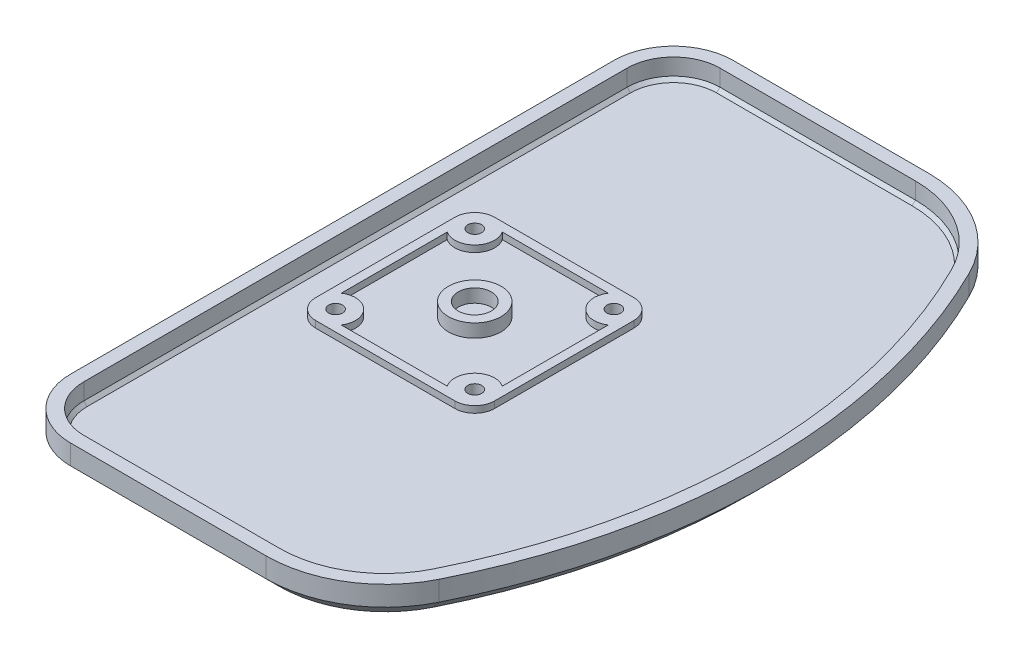
SolidWorks part; units mm, degrees
material "ABS"
ref_plane "Front" through (0, 0, 0) normal (0, 0, 1) x (1, 0, 0)
ref_plane "Top" through (0, 0, 0) normal (0, 1, 0) x (1, 0, 0)
ref_plane "Right" through (0, 0, 0) normal (1, 0, 0) x (0, 0, -1)
sketch "ｽｹｯﾁ1" plane through (0, 0, 0) normal (0, 1, 0) x (1, 0, 0)
  line L0 (-20, 0) -> (44, 0) construction
  line L1 (-20, 50) -> (28.8331, 50)
  line L2 (-20, 50) -> (-20, -50)
  line L3 (-20, -50) -> (28.8331, -50)
  line L5 (-20, 50) -> (22.854, -57.135) construction
  line L6 (-20, -50) -> (29.8928, 74.732) construction
  arc A0 (28.8331, -50) -> (28.8331, 50) centre (-46, 0) ccw
  point P0 (0, 0)
  dimension "D2" = 180
  dimension "D3" = 0
  dimension "D1" = 100
  dimension "D4" = 64
  dimension "D5" = 0
  dimension "D6" = 20
extrude "ﾎﾞｽ - 押し出し1" add sketch "ｽｹｯﾁ1" along normal blind 5
fillet "ﾌｨﾚｯﾄ1" radius 9 2 edges at (-20, 2.5, -50) (-20, 2.5, 50)
fillet "ﾌｨﾚｯﾄ2" radius 18 2 edges at (28.8331, 2.5, -50) (28.8331, 2.5, 50)
shell "ｼｪﾙ1" thickness 2
chamfer "面取り1" distance 0.5 angle 45 8 edges at (26.9308, 2, 45.5974) (3.749, 2, 48) (42, 2, 0) (-15.9497, 2, 45.9497) (26.9308, 2, -45.5974) (-18, 2, 0) (3.749, 2, -48) (-15.9497, 2, -45.9497)
chamfer "面取り2" distance 2 angle 45 8 edges at (44, 0, 0) (27.9849, 0, -47.2971) (27.9849, 0, 47.2971) (3.749, 0, -50) (3.749, 0, 50) (-17.364, 0, -47.364) (-17.364, 0, 47.364) (-20, 0, 0)
sketch "ｽｹｯﾁ2" plane through (0, 2, 0) normal (0, 1, 0) x (1, 0, 0)
  line L1 (-13.5, 13.5) -> (13.5, 13.5)
  line L2 (-13.5, 13.5) -> (-13.5, -13.5)
  line L3 (-13.5, -13.5) -> (13.5, -13.5)
  line L4 (13.5, 13.5) -> (13.5, -13.5)
  line L5 (-13.5, 13.5) -> (13.5, -13.5) construction
  line L6 (-13.5, -13.5) -> (13.5, 13.5) construction
  point P0 (0, 0)
  dimension "D1" = 27
  dimension "D2" = 27
extrude "ﾎﾞｽ - 押し出し2" add sketch "ｽｹｯﾁ2" along normal blind 1
sketch "ｽｹｯﾁ3" plane through (0, 3, 0) normal (0, 1, 0) x (1, 0, 0)
  circle A0 centre (0, 0) radius 3.975
  dimension "D1" = 7.95
extrude "ﾎﾞｽ - 押し出し3" add sketch "ｽｹｯﾁ3" along normal blind 1
fillet "ﾌｨﾚｯﾄ3" radius 3 4 edges at (-13.5, 2.5, -13.5) (13.5, 2.5, -13.5) (13.5, 2.5, 13.5) (-13.5, 2.5, 13.5)
hole_wizard "M2 なべ頭ねじ用座ぐり穴1" positions "ｽｹｯﾁ4" profile "ｽｹｯﾁ5" counterbore size "M2" standard "ISO" end condition up to next
sketch "ｽｹｯﾁ4" plane through (0, 0, 0) normal (0, -1, 0) x (-1, 0, 0)
  point P0 (10.5, 10.5)
  dimension "D1" = 10.5
  dimension "D2" = 10.5
sketch "ｽｹｯﾁ5" plane through (-10.5, 0, -10.5) normal (1, 0, 0) x (0, 0, -1)
  line L0 (0, 0) -> (0, 3)
  line L1 (0, 3) -> (1.05, 3)
  line L3 (1.05, 3) -> (1.05, 1)
  line L4 (1.05, 1) -> (1.9, 1)
  line L5 (1.9, 1) -> (1.9, 0)
  line L7 (1.9, 0) -> (0, 0)
  line L11 (0, -6.35) -> (0, 107.95) construction
  dimension "通し穴の直径" = 2.1
  dimension "通し穴の深さ" = 3
  dimension "座ぐり穴の直径" = 3.8
  dimension "座ぐり穴の深さ" = 1
pattern_circular "円形ﾊﾟﾀｰﾝ1" count 4 over 360 about axis through (0, 0, 0) along (0, 1, 0) of "M2 なべ頭ねじ用座ぐり穴1"
sketch "ｽｹｯﾁ6" plane through (0, 3, 0) normal (0, 1, 0) x (1, 0, 0)
  line L0 (-13.5, 10.5) -> (-13.5, -10.5) construction
  line L1 (12.15, -12.15) -> (-12.15, -12.15)
  line L2 (12.15, -12.15) -> (12.15, 12.15)
  line L3 (12.15, 12.15) -> (-12.15, 12.15)
  line L4 (-12.15, -12.15) -> (-12.15, 12.15)
  line L5 (12.15, -12.15) -> (-12.15, 12.15) construction
  line L6 (12.15, 12.15) -> (-12.15, -12.15) construction
  circle A0 centre (-10.5, 10.5) radius 3
  circle A1 centre (10.5, 10.5) radius 3
  circle A2 centre (-10.5, -10.5) radius 3
  circle A3 centre (10.5, -10.5) radius 3
  circle A4 centre (0, 0) radius 3.975
  point P12 (0, 0)
  circle M7 centre (0, 0) radius 3.975
  dimension "D1" = 6
  dimension "D2" = 6
  dimension "D3" = 6
  dimension "D4" = 6
  dimension "D6" = 7.95
  dimension "D5" = 1.35
extrude "ｶｯﾄ - 押し出し1" cut sketch "ｽｹｯﾁ6" against normal up to surface (1 mm away) contours A3 L2 A1 L3 A0 L4 A2 L1 M7
sketch "ｽｹｯﾁ7" plane through (0, 4, 0) normal (0, 1, 0) x (1, 0, 0)
  circle A0 centre (0, 0) radius 2.5
  dimension "D1" = 5
extrude "ｶｯﾄ - 押し出し2" cut sketch "ｽｹｯﾁ7" against normal up to surface (2 mm away) up to face at (0, 2, 3.975)
